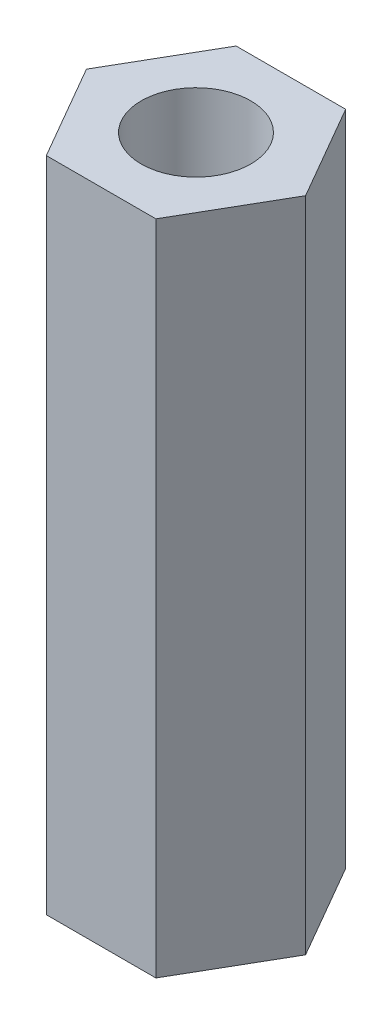
SolidWorks part; units mm, degrees
ref_plane "前视基准面" through (0, 0, 0) normal (0, 0, 1) x (1, 0, 0)
ref_plane "上视基准面" through (0, 0, 0) normal (0, 1, 0) x (1, 0, 0)
ref_plane "右视基准面" through (0, 0, 0) normal (1, 0, 0) x (0, 0, -1)
other "Configuration Table"
sketch "草图1" plane through (0, 0, 0) normal (0, 1, 0) x (1, 0, 0)
  line L1 (5, 0) -> (2.5, 4.3301)
  line L2 (2.5, 4.3301) -> (-2.5, 4.3301)
  line L3 (-2.5, 4.3301) -> (-5, 0)
  line L4 (-5, 0) -> (-2.5, -4.3301)
  line L5 (-2.5, -4.3301) -> (2.5, -4.3301)
  line L6 (2.5, -4.3301) -> (5, 0)
  circle A0 centre (0, 0) radius 4.3301 construction
  circle A1 centre (0, 0) radius 2.5
  dimension "D1" = 5
  dimension "D2" = 5
extrude "凸台-拉伸1" add sketch "草图1" along normal blind 30
